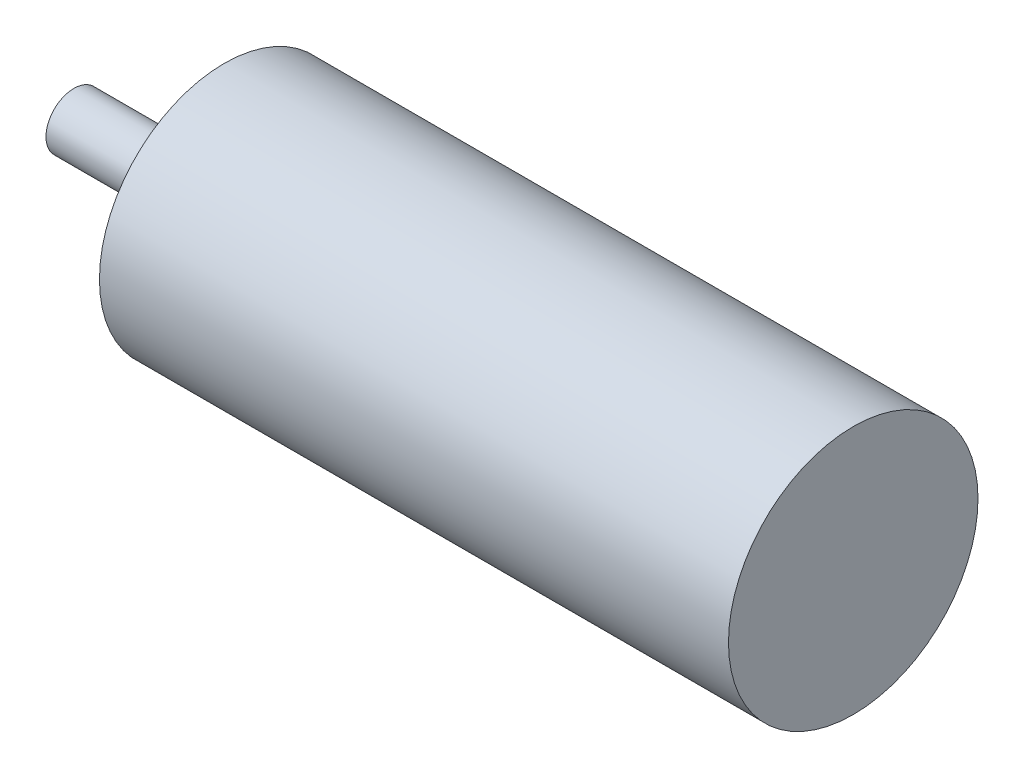
SolidWorks part; units mm, degrees
ref_plane "Front Plane" through (0, 0, 0) normal (0, 0, 1) x (1, 0, 0)
ref_plane "Top Plane" through (0, 0, 0) normal (0, 1, 0) x (1, 0, 0)
ref_plane "Right Plane" through (0, 0, 0) normal (1, 0, 0) x (0, 0, -1)
sketch "Sketch1" plane through (0, 0, 0) normal (0, 0, 1) x (1, 0, 0)
  line L0 (0, 0) -> (0, 4)
  line L1 (0, 4) -> (20, 4)
  line L2 (20, 4) -> (20, 11)
  line L3 (20, 11) -> (21.5, 11)
  line L4 (21.5, 11) -> (21.5, 17.85)
  line L5 (21.5, 17.85) -> (111.5, 17.85)
  line L6 (111.5, 17.85) -> (111.5, 0)
  line L7 (111.5, 0) -> (0, 0)
  dimension "D1" = 4
  dimension "D2" = 11
  dimension "20" = 20
  dimension "D3" = 1.5
  dimension "D4" = 17.85
  dimension "D5" = 90
revolve "Revolve1" add sketch "Sketch1" angle 360 about L7
sketch "Sketch2" plane through (21.5, 0, 0) normal (-1, 0, 0) x (0, 0, 1)
  circle A0 centre (0, 14) radius 1.5
  circle A1 centre (14, 0) radius 1.5
  circle A2 centre (0, -14) radius 1.5
  circle A3 centre (-14, 0) radius 1.5
  point P2 (-14.9654, -3.9024)
  point P4 (0, 0)
  point P12 (0, 0)
  dimension "D2" = 3
  dimension "D1" = 14
  dimension "D3" = 4
extrude "Cut-Extrude1" cut sketch "Sketch2" against normal blind 10
